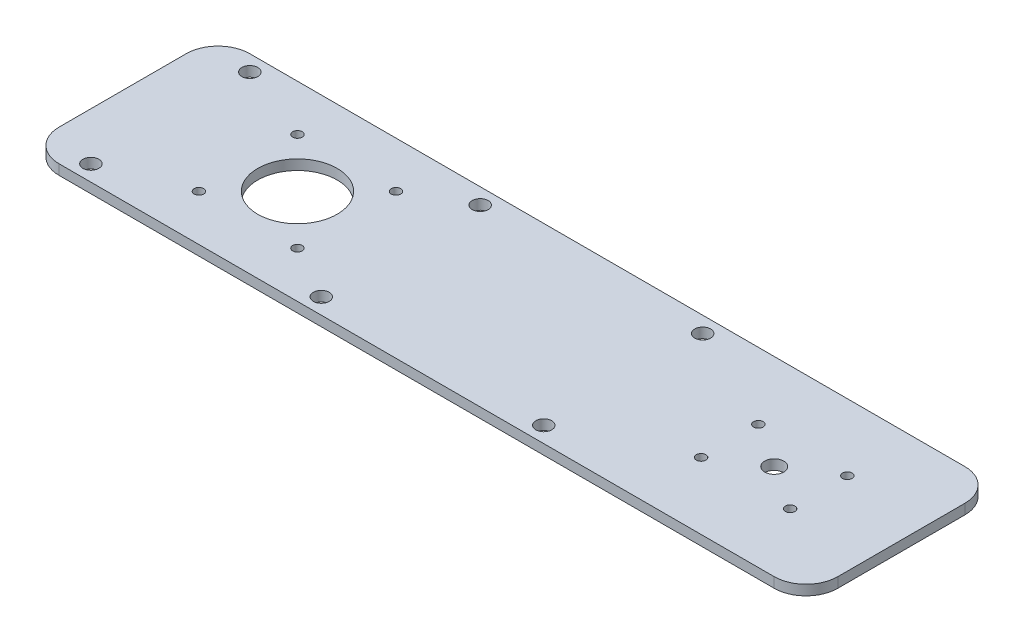
SolidWorks part; units mm, degrees
ref_plane "Front Plane" through (0, 0, 0) normal (0, 0, 1) x (1, 0, 0)
ref_plane "Top Plane" through (0, 0, 0) normal (0, 1, 0) x (1, 0, 0)
ref_plane "Right Plane" through (0, 0, 0) normal (1, 0, 0) x (0, 0, -1)
sketch "Sketch1" plane through (0, 0, 0) normal (0, 1, 0) x (1, 0, 0)
  line L0 (-55, 0) -> (0, 0) construction
  line L1 (-55, 30) -> (190, 30)
  line L2 (-55, 30) -> (-55, -30)
  line L3 (-55, -30) -> (190, -30)
  line L4 (190, 30) -> (190, -30)
  point P7 (150, 0)
  dimension "D1" = 60
  dimension "D2" = 55
  dimension "D3" = 150
  dimension "D4" = 40
extrude "Boss-Extrude1" add sketch "Sketch1" along normal blind 3.175
fillet "Fillet1" radius 10 4 edges at (-55, 1.5875, 30) (-55, 1.5875, -30) (190, 1.5875, 30) (190, 1.5875, -30)
hole_wizard "Ø3.0mm Dowel Hole1" positions "Sketch3" profile "Sketch5" hole size "Ø3.0" standard "DIN" end condition up to next
sketch "Sketch3" plane through (0, 3.175, 0) normal (0, 1, 0) x (1, 0, 0)
  point P0 (-15.5, 15.5)
  point P29 (15.5, 15.5)
  point P30 (15.5, -15.5)
  point P31 (-15.5, -15.5)
  dimension "D1" = 15.5
  dimension "D2" = 15.5
  dimension "D5" = 31
  dimension "D6" = 31
  dimension "D3" = 2
  dimension "D4" = 2
sketch "Sketch5" plane through (-15.5, 3.175, -15.5) normal (1, 0, 0) x (0, 0, 1)
  line L0 (0, 0) -> (0, 3.175)
  line L1 (0, 3.175) -> (1.5, 3.175)
  line L2 (1.5, 3.175) -> (1.5, 0)
  line L5 (1.5, 0) -> (0, 0)
  line L11 (0, -6.35) -> (0, 107.95) construction
  dimension "Thru Hole Dia." = 3
  dimension "Thru Hole Depth" = 3.175
sketch "Sketch6" plane through (0, 3.175, 0) normal (0, 1, 0) x (1, 0, 0)
  circle A0 centre (0, 0) radius 12.5
  dimension "D1" = 25
extrude "Cut-Extrude1" cut sketch "Sketch6" against normal through all
hole_wizard "Ø6.0mm Dowel Hole1" positions "Sketch7" profile "Sketch8" hole size "Ø6.0" standard "DIN" end condition up to next
sketch "Sketch7" plane through (0, 3.175, 0) normal (0, 1, 0) x (1, 0, 0)
  point P0 (150, 0)
  dimension "D1" = 150
sketch "Sketch8" plane through (150, 3.175, 0) normal (1, 0, 0) x (0, 0, 1)
  line L0 (0, 0) -> (0, 3.175)
  line L1 (0, 3.175) -> (3, 3.175)
  line L2 (3, 3.175) -> (3, 0)
  line L5 (3, 0) -> (0, 0)
  line L11 (0, -6.35) -> (0, 107.95) construction
  dimension "Thru Hole Dia." = 6
  dimension "Thru Hole Depth" = 3.175
hole_wizard "Ø3.0mm Dowel Hole2" positions "Sketch10" profile "Sketch11" hole size "Ø3.0" standard "ANSI Metric" end condition up to next
sketch "Sketch10" plane through (0, 0, 0) normal (0, -1, 0) x (-1, 0, 0)
  line L0 (-164, 9) -> (-136, 9) construction
  circle A0 centre (-150, 0) radius 3 construction
  point P0 (-164, 9)
  point P7 (-136, 9)
  point P8 (-136, -9)
  point P9 (-164, -9)
  dimension "D4" = 14
  dimension "D5" = 9
  dimension "D3" = 28
  dimension "D6" = 18
  dimension "D1" = 2
  dimension "D2" = 2
sketch "Sketch11" plane through (164, 0, -9) normal (1, 0, 0) x (0, 0, -1)
  line L0 (0, 0) -> (0, 3.175)
  line L1 (0, 3.175) -> (1.5, 3.175)
  line L2 (1.5, 3.175) -> (1.5, 0)
  line L5 (1.5, 0) -> (0, 0)
  line L11 (0, -6.35) -> (0, 107.95) construction
  dimension "Thru Hole Dia." = 3
  dimension "Thru Hole Depth" = 3.175
hole_wizard "Ø5.0mm Dowel Hole1" positions "Sketch12" profile "Sketch13" hole size "Ø5.0" standard "DIN" end condition through all
sketch "Sketch12" plane through (0, 3.175, 0) normal (0, 1, 0) x (1, 0, 0)
  line L0 (-45, -30) -> (180, -30) construction
  line L1 (32.5, -25) -> (102.5, -25) construction
  line L2 (-55, 0) -> (190, 0) construction
  line L3 (-55, 20) -> (-55, -20) construction
  line L4 (190, -20) -> (190, 20) construction
  line L5 (67.5, 30) -> (67.5, -30) construction
  line L6 (180, 30) -> (-45, 30) construction
  line L9 (67.5, -25) -> (32.5, -25) construction
  line L11 (67.5, 25) -> (102.5, 25) construction
  line L13 (67.5, 25) -> (32.5, 25) construction
  point P0 (32.5, -25)
  point P14 (102.5, -25)
  point P26 (102.5, 25)
  point P27 (32.5, 25)
  point P28 (-40, -25)
  point P31 (-40, 25)
  dimension "D1" = 5
  dimension "D4" = 70
  dimension "D5" = 15
  dimension "D3" = 2
sketch "Sketch13" plane through (32.5, 3.175, 25) normal (1, 0, 0) x (0, 0, 1)
  line L0 (0, 0) -> (0, 3.175)
  line L1 (0, 3.175) -> (2.5, 3.175)
  line L2 (2.5, 3.175) -> (2.5, 0)
  line L5 (2.5, 0) -> (0, 0)
  line L11 (0, -6.35) -> (0, 107.95) construction
  dimension "Thru Hole Dia." = 5
  dimension "Thru Hole Depth" = 3.175
equation "\"Pivot to Pivot Dist\"= 150"
equation "\"D3@Sketch1\"=\"Pivot to Pivot Dist\""
equation "\"D1@Sketch7\"=\"Pivot to Pivot Dist\""
